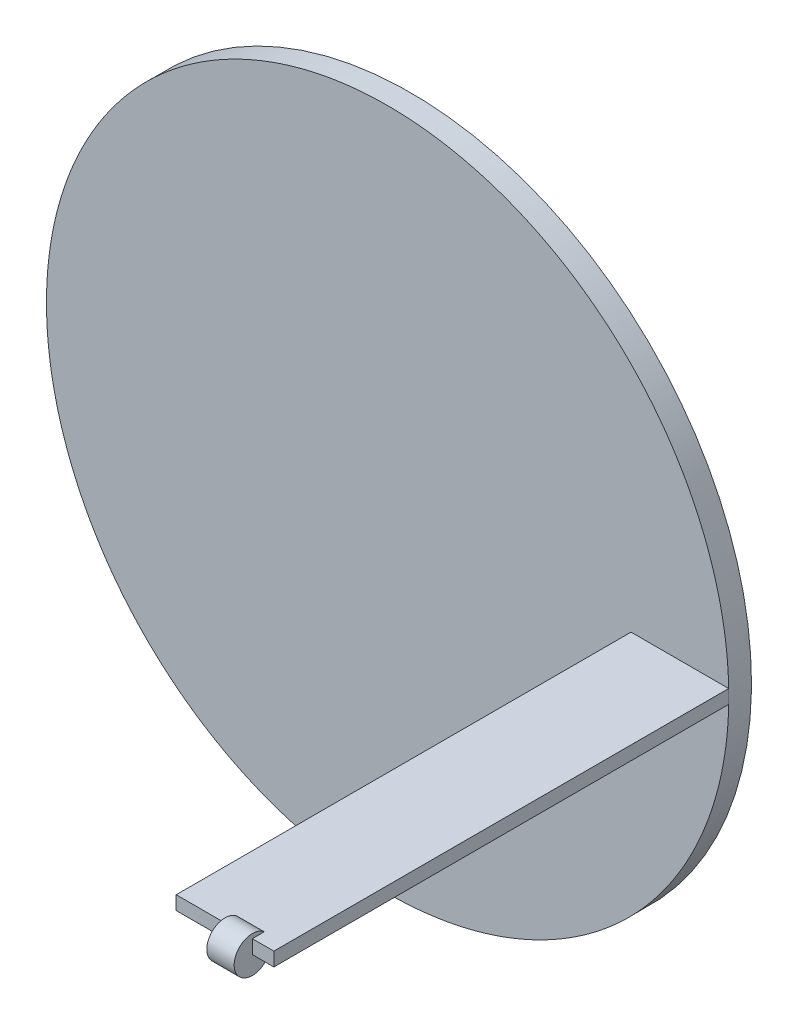
SolidWorks part; units mm, degrees
ref_plane "Plano frontal" through (0, 0, 0) normal (1, 0, 0) x (0, 1, 0)
ref_plane "Plano superior" through (0, 0, 0) normal (0, 0, 1) x (0, 1, 0)
ref_plane "Plano direito" through (0, 0, 0) normal (0, 1, 0) x (-1, 0, 0)
sketch "Esboço1" plane through (0, 0, 0) normal (0, 0, 1) x (0, 1, 0)
  circle A0 centre (0, 0) radius 75
extrude "Ressalto-extrusão1" add sketch "Esboço1" along normal blind 5
sketch "Esboço2" plane through (0, 0, 5) normal (0, 0, 1) x (1, 0, 0)
  circle A0 centre (0, 0) radius 10
extrude "Ressalto-extrusão2" add sketch "Esboço2" against normal blind 30
sketch "Esboço4" plane through (0, 0, 5) normal (0, 0, 1) x (1, 0, 0)
  line L1 (74.9846, -1.5182) -> (53.5162, -1.5182)
  line L2 (74.9846, -1.5182) -> (74.9846, 1.505)
  line L3 (74.9846, 1.505) -> (53.5162, 1.505)
  line L4 (53.5162, -1.5182) -> (53.5162, 1.505)
  circle A0 centre (0, 0) radius 75 construction
extrude "Ressalto-extrusão3" add sketch "Esboço4" along normal blind 100
sketch3d "SMLINK_BETA_AXIS"
  line L0 (0, 0, -50) -> (0, 0, 0) construction
  point P0 (0, 0, -25)
sketch3d "SMLINK_PSI_AXIS"
  line L0 (39.2504, -1.5182, 105) -> (89.2504, -1.5182, 105) construction
  point P0 (64.2504, -1.5182, 105)
ref_plane "SMLINK_BETA_PLANE" through (0, 0, -25) normal (0, 0, 1) x (0, 1, 0)
sketch "SMLINK_BETA_CIRCLE" plane through (0, 0, -25) normal (0, 0, 1) x (0, 1, 0)
  circle A0 centre (0, 0) radius 4
extrude "SMLINK_BETA_CYLINDER" add sketch "SMLINK_BETA_CIRCLE" against normal blind 6 separate body
ref_plane "SMLINK_PSI_PLANE" through (64.2504, 0, 0) normal (1, 0, 0) x (0, 1, 0)
sketch "SMLINK_PSI_CIRCLE" plane through (64.2504, 0, 0) normal (1, 0, 0) x (0, 1, 0)
  circle A0 centre (-1.5182, 105) radius 4
extrude "SMLINK_PSI_CYLINDER" add sketch "SMLINK_PSI_CIRCLE" along normal blind 6 separate body
